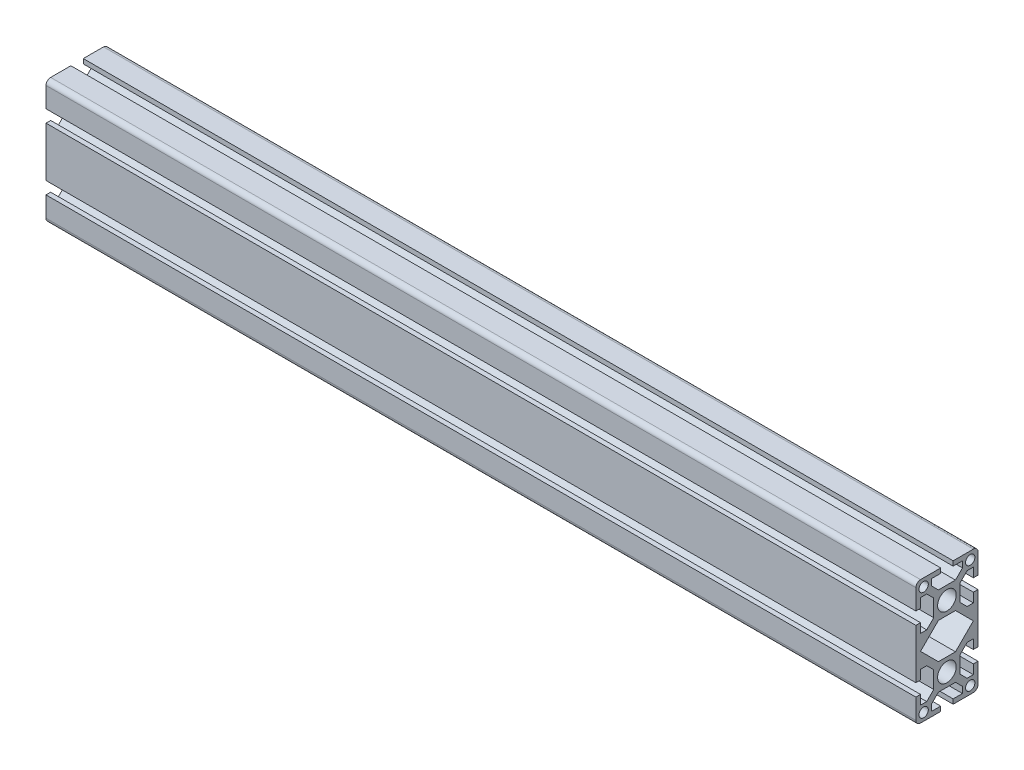
SolidWorks part; units mm, degrees
ref_plane "Front Plane" through (0, 0, 0) normal (0, 0, 1) x (1, 0, 0)
ref_plane "Top Plane" through (0, 0, 0) normal (0, 1, 0) x (1, 0, 0)
ref_plane "Right Plane" through (0, 0, 0) normal (1, 0, 0) x (0, 0, -1)
sketch "Sketch1" plane through (0, 0, 0) normal (1, 0, 0) x (0, 0, -1)
  line L0 (-20, -4) -> (-17, -4)
  line L1 (20, 0) -> (-20, 0) construction
  line L2 (0, 60) -> (0, -20) construction
  line L3 (-4, -20) -> (-17, -20)
  line L4 (-20, -4) -> (-20, -17)
  line L5 (-17, -4) -> (-17, -10)
  line L6 (-17, -10) -> (-13, -10)
  line L7 (-13, -10) -> (-8.5, -5.5)
  line L8 (-8.5, -5.5) -> (-8.5, 5.5)
  line L9 (-20, -20) -> (0, 0) construction
  line L10 (-5.5, -8.5) -> (5.5, -8.5)
  line L11 (-10, -13) -> (-5.5, -8.5)
  line L12 (-10, -17) -> (-10, -13)
  line L13 (-4, -17) -> (-10, -17)
  line L14 (-4, -20) -> (-4, -17)
  line L15 (-20, 20) -> (0, 0) construction
  line L16 (-20, 20) -> (20, 20) construction
  line L17 (-5.5, 8.5) -> (-17, 20)
  line L18 (5.5, 8.5) -> (17, 20)
  line L19 (20, 60) -> (0, 40) construction
  line L20 (-20, 60) -> (0, 40) construction
  line L21 (-5.5, 8.5) -> (5.5, 8.5)
  line L22 (-13, 10) -> (-8.5, 5.5)
  line L23 (-17, 10) -> (-13, 10)
  line L24 (-17, 4) -> (-17, 10)
  line L25 (-20, 4) -> (-20, 36)
  line L26 (-20, 4) -> (-17, 4)
  line L27 (20, 20) -> (0, 0) construction
  line L28 (20, -20) -> (0, 0) construction
  line L29 (20, 4) -> (17, 4)
  line L30 (4, 60) -> (4, 57)
  line L31 (20, 4) -> (20, 20)
  line L32 (17, 4) -> (17, 10)
  line L33 (17, 10) -> (13, 10)
  line L34 (13, 10) -> (8.5, 5.5)
  line L35 (4, 60) -> (17, 60)
  line L36 (-4, 60) -> (-4, 57)
  line L37 (-4, 60) -> (-17, 60)
  line L38 (20, 20) -> (0, 40) construction
  line L39 (4, -20) -> (17, -20)
  line L40 (4, -20) -> (4, -17)
  line L41 (4, -17) -> (10, -17)
  line L42 (10, -17) -> (10, -13)
  line L43 (10, -13) -> (5.5, -8.5)
  line L44 (8.5, -5.5) -> (8.5, 5.5)
  line L45 (13, -10) -> (8.5, -5.5)
  line L46 (17, -10) -> (13, -10)
  line L47 (17, -4) -> (17, -10)
  line L48 (20, -4) -> (20, -17)
  line L49 (20, -4) -> (17, -4)
  line L50 (-20, 20) -> (0, 40) construction
  line L51 (20, 40) -> (-20, 40) construction
  line L52 (20, 44) -> (17, 44)
  line L53 (20, 44) -> (20, 57)
  line L54 (17, 44) -> (17, 50)
  line L55 (17, 50) -> (13, 50)
  line L56 (13, 50) -> (8.5, 45.5)
  line L57 (8.5, 45.5) -> (8.5, 34.5)
  line L58 (10, 53) -> (5.5, 48.5)
  line L59 (10, 57) -> (10, 53)
  line L60 (4, 57) -> (10, 57)
  line L61 (13, 30) -> (8.5, 34.5)
  line L62 (17, 30) -> (13, 30)
  line L63 (17, 36) -> (17, 30)
  line L64 (20, 36) -> (20, 20)
  line L65 (20, 36) -> (17, 36)
  line L66 (-20, 36) -> (-17, 36)
  line L67 (-17, 36) -> (-17, 30)
  line L68 (-17, 30) -> (-13, 30)
  line L69 (-13, 30) -> (-8.5, 34.5)
  line L70 (-5.5, 31.5) -> (5.5, 31.5)
  line L71 (5.5, 31.5) -> (17, 20)
  line L72 (-5.5, 31.5) -> (-17, 20)
  line L73 (-4, 57) -> (-10, 57)
  line L74 (-10, 57) -> (-10, 53)
  line L75 (-10, 53) -> (-5.5, 48.5)
  line L76 (-5.5, 48.5) -> (5.5, 48.5)
  line L77 (-8.5, 45.5) -> (-8.5, 34.5)
  line L78 (-13, 50) -> (-8.5, 45.5)
  line L79 (-17, 50) -> (-13, 50)
  line L80 (-17, 44) -> (-17, 50)
  line L81 (-20, 44) -> (-20, 57)
  line L82 (-20, 44) -> (-17, 44)
  circle A0 centre (0, 0) radius 6
  circle A1 centre (-15, -15) radius 3
  arc A2 (-17, -20) -> (-20, -17) centre (-17, -17) cw
  arc A3 (17, 60) -> (20, 57) centre (17, 57) cw
  arc A4 (-17, 60) -> (-20, 57) centre (-17, 57) ccw
  circle A5 centre (15, 55) radius 3
  circle A6 centre (-15, 55) radius 3
  arc A7 (17, -20) -> (20, -17) centre (17, -17) ccw
  circle A8 centre (15, -15) radius 3
  circle A9 centre (0, 40) radius 6
  point P33 (0, 20)
  point P37 (-8.5, 0)
  point P60 (0, 8.5)
  point P68 (0, -8.5)
  point P73 (8.5, 0)
  point P110 (8.5, 40)
  point P111 (0, 48.5)
  point P112 (0, 31.5)
  point P113 (-8.5, 40)
  dimension "D1" = 12
  dimension "D4" = 3
  dimension "D5" = 6
  dimension "D2" = 20
  dimension "D3" = 20
  dimension "D6" = 5
  dimension "D7" = 5
  dimension "D8" = 3
  dimension "D9" = 10
  dimension "D10" = 8.5
  dimension "D11" = 45
  dimension "D12" = 16
  dimension "D13" = 4
  dimension "D14" = 45
extrude "Boss-Extrude1" add sketch "Sketch1" along normal blind 560 contours L39 A7 L48 L49 L47 L46 L45 L44 L34 L33 L32 L29 L31 L64 L65 L63 L62 L61 L57 L56 L55 L54 L52 L53 A3 L35 L30 L60 L59 L58 L76 L75 L74 L73 L36 L37 A4 L81 L82 L80 L79 L78 L77 L69 L68 L67 L66 L25 L26 L24 L23
